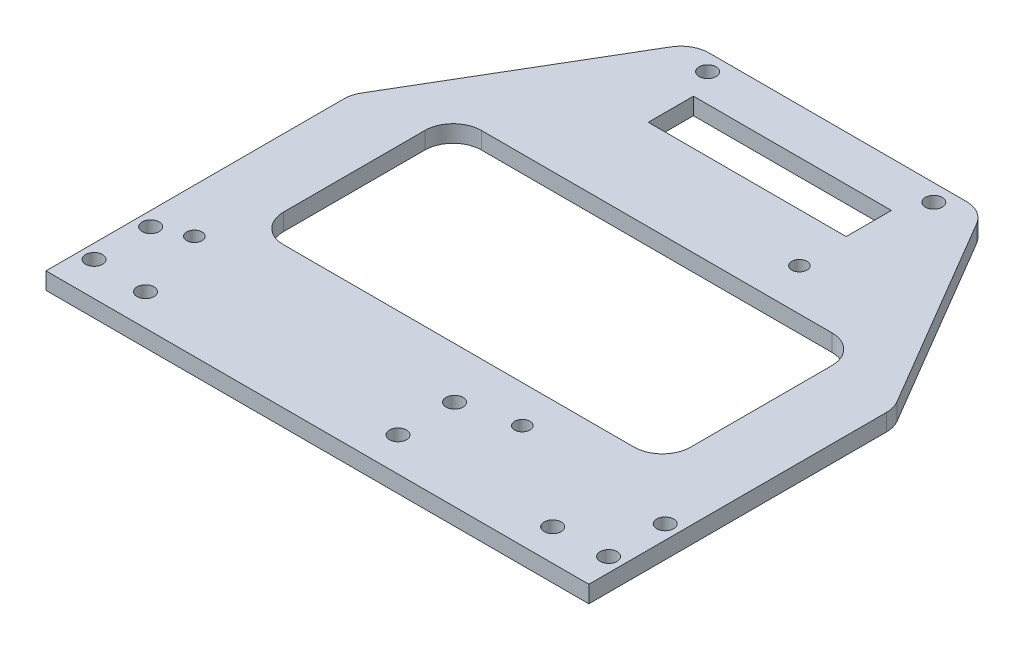
SolidWorks part; units mm, degrees
ref_plane "前基準面" through (0, 0, 0) normal (0, 0, 1) x (1, 0, 0)
ref_plane "上基準面" through (0, 0, 0) normal (0, 1, 0) x (1, 0, 0)
ref_plane "右基準面" through (0, 0, 0) normal (1, 0, 0) x (0, 0, -1)
sketch "Sketch1" plane through (0, 0, 0) normal (0, 1, 0) x (1, 0, 0)
  line L0 (43, -58) -> (48, -58) construction
  line L1 (-48, -80) -> (48, -80) construction
  line L2 (-48, -80) -> (-48, 80)
  line L3 (-48, 80) -> (48, 80)
  line L4 (48, -80) -> (48, 80)
  line L5 (0, 80) -> (0, -80) construction
  line L6 (-48, 0) -> (48, 0) construction
  line L7 (-48, -80) -> (48, -80) construction
  line L8 (-48, -80) -> (-48, -96)
  line L9 (-48, -96) -> (48, -96)
  line L10 (48, -80) -> (48, -96)
  line L11 (19.5, -31.4) -> (25.5, -31.4)
  line L12 (19.5, -31.4) -> (19.5, -59.4)
  line L13 (19.5, -59.4) -> (25.5, -59.4)
  line L14 (25.5, -31.4) -> (25.5, -59.4)
  line L15 (43, -80) -> (34.5, -80)
  line L16 (43, -80) -> (43, -31.4) construction
  line L17 (43, -31.4) -> (34.5, -31.4)
  line L18 (34.5, -80) -> (34.5, -31.4)
  line L19 (43, -31.4) -> (43.5, -31.4)
  line L20 (43, -31.4) -> (43, -58) construction
  line L21 (43, -58) -> (43.5, -58)
  line L22 (43.5, -31.4) -> (43.5, -58)
  line L23 (43, -80) -> (43, -58)
  circle A0 centre (45.5, -74) radius 1.5 construction
  circle A1 centre (45.5, -64) radius 1.5 construction
  circle A2 centre (-45.5, -64) radius 1.5 construction
  circle A3 centre (-45.5, -74) radius 1.5 construction
  circle A4 centre (45.5, -74) radius 1.5
  circle A5 centre (45.5, -64) radius 1.5
  circle A6 centre (-45.5, -64) radius 1.5
  circle A7 centre (-45.5, -74) radius 1.5
  circle A8 centre (8.25, -74) radius 1.5 construction
  circle A9 centre (8.25, -64) radius 1.5 construction
  circle A10 centre (8.25, -74) radius 1.5
  circle A11 centre (8.25, -64) radius 1.5
  circle A12 centre (15.3209, -52.5307) radius 1.65 construction
  circle A13 centre (0.2595, -52.5307) radius 1.65 construction
  circle A14 centre (15.3209, -37.4693) radius 1.65 construction
  circle A15 centre (0.2595, -37.4693) radius 1.65 construction
  circle A16 centre (15.3209, -52.5307) radius 1.65 construction
  circle A17 centre (0.2595, -52.5307) radius 1.65 construction
  circle A18 centre (15.3209, -37.4693) radius 1.65 construction
  circle A19 centre (0.2595, -37.4693) radius 1.65 construction
  circle A24 centre (0.2595, -37.4693) radius 1.65
  circle A25 centre (15.3209, -37.4693) radius 1.65
  circle A26 centre (15.3209, -52.5307) radius 1.65
  circle A27 centre (0.2595, -52.5307) radius 1.65
  circle A28 centre (17.55, -90) radius 1.5 construction
  circle A29 centre (17.55, -90) radius 1.5
  circle A30 centre (45.55, -90) radius 1.5 construction
  circle A31 centre (45.55, -90) radius 1.5
  circle A32 centre (-45.55, -90) radius 1.5
  circle A33 centre (-17.55, -90) radius 1.5
  point P0 (0, 0)
  dimension "D4" = 0.5
  dimension "D5" = 6
  dimension "D1" = 96
  dimension "D2" = 160
  dimension "D3" = 16
  dimension "D6" = 28
  dimension "D7" = 22.5
  dimension "D8" = 36.6
  dimension "D9" = 8.5
  dimension "D10" = 48.6
extrude "Boss-Extrude1" add sketch "Sketch1" along normal blind 3
sketch "Sketch3" plane through (0, 3, 0) normal (0, 1, 0) x (1, 0, 0)
  line L0 (0, -96) -> (0, 80) construction
  line L1 (-48, -96) -> (48, -96) construction
  line L2 (48, 80) -> (-48, 80) construction
  line L3 (0, 9) -> (-17.8495, 79.2684) construction
  line L4 (-17.8495, 79.2684) -> (17.8495, 79.2684) construction
  line L5 (0, 9) -> (17.8495, 79.2684) construction
  circle A0 centre (0, 9) radius 5 construction
  circle A1 centre (0, 9) radius 1.5
  circle A2 centre (-17.8495, 79.2684) radius 0.7646 construction
  circle A3 centre (17.8495, 79.2684) radius 1.5 construction
  point P12 (0, 79.2684)
  dimension "D1" = 10
  dimension "D2" = 105
  dimension "D3" = 3
  dimension "D6" = 3
  dimension "D7" = 1.5291
  dimension "D4" = 72.5
  dimension "D5" = 17.8495
extrude "Cut-Extrude2" cut sketch "Sketch3" against normal up to next
sketch "Sketch4" plane through (0, 3, 0) normal (0, 1, 0) x (1, 0, 0)
  line L0 (0, 80) -> (0, 0) construction
  line L1 (48, 80) -> (-48, 80) construction
  line L2 (48, 12) -> (25.605, 12)
  line L3 (-48, 80) -> (-25.605, 80)
  line L4 (-48, 80) -> (-48, 12)
  line L5 (-48, 12) -> (-25.605, 12)
  line L6 (-25.605, 80) -> (-25.605, 12)
  line L7 (25.605, 80) -> (25.605, 12)
  line L8 (48, 80) -> (25.605, 80)
  line L9 (48, 80) -> (48, 12)
  dimension "D1" = 51.21
  dimension "D2" = 68
extrude "Cut-Extrude3" cut sketch "Sketch4" against normal up to next
sketch "Sketch6" plane through (0, 3, 0) normal (0, 1, 0) x (1, 0, 0)
  line L0 (25.605, 80) -> (25.605, 12) construction
  line L1 (-25.605, 80) -> (25.605, 80)
  line L2 (-25.605, 80) -> (-25.605, 85)
  line L3 (-25.605, 85) -> (25.605, 85)
  line L4 (25.605, 80) -> (25.605, 85)
  dimension "D1" = 5
extrude "Boss-Extrude2" add sketch "Sketch6" against normal blind 3
sketch "Sketch7" plane through (0, 3, 0) normal (0, 1, 0) x (1, 0, 0)
  circle A0 centre (-17.8495, 79.2684) radius 1.5
  circle A1 centre (17.8495, 79.2684) radius 1.5
  dimension "D1" = 3
  dimension "D2" = 3
extrude "Cut-Extrude4" cut sketch "Sketch7" against normal up to next
sketch "Sketch9" plane through (0, 3, 0) normal (0, 1, 0) x (1, 0, 0)
  line L2 (25.605, 85) -> (-25.605, 85) construction
  line L4 (-22.6908, 44) -> (-25.605, 44) construction
  line L5 (-25.605, 12) -> (-25.605, 85) construction
  line L6 (-22.6908, 44) -> (-22.6908, 32.9821) construction
  line L7 (0, 85) -> (0, 0) construction
  circle A1 centre (-22.6908, 44) radius 1.5
  circle A2 centre (22.6908, 44) radius 1.5
  dimension "D1" = 3
  dimension "D2" = 41
extrude "Cut-Extrude5" cut sketch "Sketch9" against normal up to next
sketch "Sketch10" plane through (0, 3, 0) normal (0, 1, 0) x (1, 0, 0)
  line L0 (0, 85) -> (0, -96) construction
  line L1 (25.605, 85) -> (-25.605, 85) construction
  line L2 (-48, -96) -> (48, -96) construction
  line L3 (48, -26) -> (25.605, 12)
  line L4 (48, -96) -> (48, 12) construction
  line L5 (48, -26) -> (48, 12)
  line L6 (48, 12) -> (25.605, 12)
  line L7 (-48, -26) -> (-48, 12)
  line L8 (-48, -26) -> (-25.605, 12)
  line L9 (-48, 12) -> (-25.605, 12)
  dimension "D1" = 38
extrude "Cut-Extrude6" cut sketch "Sketch10" against normal up to next
sketch "Sketch11" plane through (0, 0, 0) normal (0, -1, 0) x (1, 0, 0)
  line L0 (-25.605, -52.6413) -> (-45.8738, -40.3515)
  line L1 (-45.8738, -40.3515) -> (-25.605, -52.6413) construction
  line L2 (-42.8854, -33.0371) -> (-31.7967, -35.6413)
  line L3 (-31.7967, -35.6413) -> (-25.605, -35.6413)
  line L4 (-16.2499, -35.6413) -> (-31.7967, -35.6413) construction
  line L5 (-25.605, -35.6413) -> (-25.605, -52.6413)
  line L6 (0, 0) -> (0, -85) construction
  line L7 (42.8854, -33.0371) -> (31.7967, -35.6413)
  line L8 (25.605, -12) -> (48, 26)
  line L9 (48, 26) -> (48, 96)
  line L10 (48, 96) -> (-48, 96)
  line L11 (-48, 96) -> (-48, 26)
  line L12 (-48, 26) -> (-25.605, -12)
  line L13 (-25.605, -12) -> (-25.605, -85)
  line L14 (-25.605, -85) -> (25.605, -85)
  line L15 (25.605, -85) -> (25.605, -12)
  line L16 (25.605, -12) -> (48, 26)
  line L17 (48, 26) -> (48, 96)
  line L18 (48, 96) -> (-48, 96)
  line L19 (-48, 96) -> (-48, 26)
  line L20 (-48, 26) -> (-25.605, -12)
  line L21 (-25.605, -12) -> (-25.605, -85)
  line L22 (-25.605, -85) -> (25.605, -85)
  line L23 (25.605, -85) -> (25.605, -12)
  line L24 (31.7967, -35.6413) -> (25.605, -35.6413)
  line L25 (25.605, -35.6413) -> (25.605, -52.6413)
  line L26 (25.605, -52.6413) -> (45.8738, -40.3515)
  arc A0 (-45.8738, -40.3515) -> (-42.8854, -33.0371) centre (-43.7999, -36.9312) cw
  circle A1 centre (-43.7999, -36.9312) radius 2.5
  circle A2 centre (-32.9303, -41.9312) radius 1.5
  circle A3 centre (32.9303, -41.9312) radius 1.5
  circle A4 centre (43.7999, -36.9312) radius 2.5
  arc A5 (45.8738, -40.3515) -> (42.8854, -33.0371) centre (43.7999, -36.9312) ccw
  line M26 (-25.605, -12) -> (-25.605, -85)
  dimension "D2" = 5
  dimension "D3" = 3
  dimension "D1" = 0
extrude "Boss-Extrude3" add sketch "Sketch11" against normal blind 3 contours A0 L0 L3 L2 A2 A1 M26 | L26 A5 L7 L24 L23 A4 A3
sketch "Sketch12" plane through (0, 0, 0) normal (0, -1, 0) x (1, 0, 0)
  line L0 (11.4001, -53.9413) -> (11.4001, -38.6413) construction
  line L1 (11.4001, -38.6413) -> (16.2501, -38.6413) construction
  line L2 (16.2501, -38.6413) -> (16.3501, -32.8413) construction
  line L3 (16.3501, -32.8413) -> (11.4001, -32.8413) construction
  line L4 (11.4001, -32.8413) -> (11.4001, -31.1913) construction
  line L5 (11.4001, -31.1913) -> (11.4001, -25.1913) construction
  line L6 (11.4001, -25.1913) -> (5.4001, -25.1913) construction
  line L7 (11.4001, -25.1913) -> (11.4001, -19.8913) construction
  line L8 (11.4001, -19.8913) -> (-2.9999, -19.8913) construction
  line L9 (-2.9999, -19.8913) -> (-2.9999, -31.1913) construction
  line L10 (-11.0999, -31.1913) -> (5.4001, -31.1913) construction
  line L11 (-2.9999, -31.1913) -> (-11.0999, -31.1913) construction
  line L12 (-11.0999, -31.1913) -> (-11.0999, -32.8413) construction
  line L13 (-11.0999, -32.8413) -> (-16.0499, -32.8413) construction
  line L14 (-16.0499, -32.8413) -> (-16.0499, -38.6413) construction
  line L15 (-15.2499, -38.6413) -> (-16.2499, -38.6413) construction
  line L16 (-16.0499, -38.6413) -> (-11.0999, -38.6413) construction
  line L17 (-11.0999, -53.9413) -> (-11.0999, -35.6413) construction
  line L18 (-11.0999, -38.6413) -> (-11.0999, -53.9413) construction
  line L19 (-11.0999, -53.9413) -> (11.4001, -53.9413) construction
  line L20 (-11.8999, -39.4413) -> (-11.8999, -54.7413)
  line L21 (-11.8999, -54.7413) -> (12.2001, -54.7413)
  line L22 (12.2001, -54.7413) -> (12.2001, -39.4413)
  line L23 (12.2001, -39.4413) -> (17.0364, -39.4413)
  line L24 (17.0364, -39.4413) -> (17.164, -32.0413)
  line L25 (17.164, -32.0413) -> (12.2001, -32.0413)
  line L26 (12.2001, -32.0413) -> (12.2001, -31.1913)
  line L27 (12.2001, -31.1913) -> (12.2001, -25.1913)
  line L28 (12.2001, -25.1913) -> (12.2001, -19.0913)
  line L29 (12.2001, -19.0913) -> (-3.7999, -19.0913)
  line L30 (-3.7999, -19.0913) -> (-3.7999, -30.3913)
  line L31 (-3.7999, -30.3913) -> (-11.8999, -30.3913)
  line L32 (-11.8999, -30.3913) -> (-11.8999, -32.0413)
  line L33 (-11.8999, -32.0413) -> (-16.8499, -32.0413)
  line L34 (-16.8499, -32.0413) -> (-16.8499, -39.4413)
  line L35 (-16.8499, -39.4413) -> (-11.8999, -39.4413)
  dimension "D2" = 16
  dimension "D3" = 11.3
  dimension "D1" = 0.8
extrude "Cut-Extrude7" cut sketch "Sketch12" against normal up to next
sketch "Sketch13" plane through (0, 0, 0) normal (0, -1, 0) x (1, 0, 0)
  line L0 (-11.8999, -39.4413) -> (-11.8999, -54.7413) construction
  line L1 (-16.8499, -29.0413) -> (-11.8999, -29.0413)
  line L2 (-16.8499, -29.0413) -> (-16.8499, -44.0413)
  line L3 (-16.8499, -44.0413) -> (-11.8999, -44.0413)
  line L4 (-11.8999, -29.0413) -> (-11.8999, -44.0413)
  line L5 (-16.8499, -32.0413) -> (-16.8499, -39.4413) construction
  line L6 (-11.8999, -32.0413) -> (-16.8499, -32.0413) construction
  line L7 (0.1501, -54.7413) -> (0.1501, -13.9321) construction
  line L8 (-11.8999, -54.7413) -> (12.2001, -54.7413) construction
  line L9 (17.1501, -29.0413) -> (17.1501, -44.0413)
  line L10 (17.1501, -29.0413) -> (12.2001, -29.0413)
  line L11 (12.2001, -29.0413) -> (12.2001, -44.0413)
  line L12 (17.1501, -44.0413) -> (12.2001, -44.0413)
  line L13 (12.2001, -54.7413) -> (12.2001, -39.4413) construction
  line L14 (12.2001, -51.376) -> (18.2789, -51.376)
  line L15 (12.2001, -51.376) -> (12.2001, -46.608)
  line L16 (12.2001, -46.608) -> (18.2789, -46.608)
  line L17 (18.2789, -51.376) -> (18.2789, -46.608)
  dimension "D1" = 3
  dimension "D2" = 15
extrude "Cut-Extrude8" cut sketch "Sketch13" against normal up to next
sketch "Sketch14" plane through (0, 0, 0) normal (0, -1, 0) x (1, 0, 0)
  line L0 (0, -85) -> (0, 0) construction
  line L1 (25.605, -85) -> (-25.605, -85) construction
  line L2 (25.605, -85) -> (25.605, -72)
  line L3 (70, -72) -> (-70, -72)
  line L4 (70, -72) -> (70, -77)
  line L5 (62, -85) -> (-62, -85)
  line L6 (-70, -72) -> (-70, -77)
  line L7 (0, -85) -> (0, -72) construction
  line L8 (70, -74.5) -> (-70, -74.5) construction
  line L9 (-25.605, -85) -> (-25.605, -72)
  arc A0 (70, -77) -> (62, -85) centre (62, -77) cw
  arc A1 (-62, -85) -> (-70, -77) centre (-62, -77) cw
  point P5 (0, -74.5)
  point P15 (70, -85)
  point P18 (-70, -85)
  dimension "D3" = 8
  dimension "D1" = 13
  dimension "D2" = 140
extrude "Boss-Extrude4" add sketch "Sketch14" against normal blind 3 contours A1 L5 L9 L3 L6 | A0 L4 L3 L2 L5
sketch "Sketch15" plane through (0, 3, 0) normal (0, 1, 0) x (1, 0, 0)
  line L0 (0, 0) -> (0, 85) construction
  line L1 (62, 85) -> (-62, 85) construction
  line L2 (20, 9) -> (-20, 9) construction
  circle A0 centre (-20, 9) radius 1.5
  circle A1 centre (20, 9) radius 1.5
  point P9 (0, 9)
  dimension "D2" = 3
  dimension "D1" = 40
extrude "Cut-Extrude9" cut sketch "Sketch15" against normal up to next
sketch "Sketch18" plane through (0, 3, 0) normal (0, 1, 0) x (1, 0, 0)
  line L0 (-25.605, 12) -> (25.605, 12)
  line L2 (83.0825, 12) -> (-87.9318, 12)
  line L3 (83.0825, 12) -> (83.0825, 92.1136)
  line L4 (83.0825, 92.1136) -> (-87.9318, 92.1136)
  line L5 (-87.9318, 12) -> (-87.9318, 92.1136)
extrude "Cut-Extrude10" cut sketch "Sketch18" against normal through all contours L5 L2 L0 L3 L4
sketch "Sketch19" plane through (0, 3, 0) normal (0, 1, 0) x (1, 0, 0)
  line L1 (43.5, -31.4) -> (34.5, -31.4)
  line L2 (43.5, -31.4) -> (43.5, -80)
  line L3 (43.5, -80) -> (34.5, -80)
  line L4 (34.5, -31.4) -> (34.5, -80)
  line L5 (25.5, -31.4) -> (-5.9684, -31.4)
  line L6 (25.5, -31.4) -> (25.5, -59.4519)
  line L7 (25.5, -59.4519) -> (-5.9684, -59.4519)
  line L8 (-5.9684, -31.4) -> (-5.9684, -59.4519)
extrude "Boss-Extrude5" add sketch "Sketch19" against normal through all
sketch "Sketch20" plane through (0, 3, 0) normal (0, 1, 0) x (1, 0, 0)
  line L0 (48, -96) -> (48, -26) construction
  line L1 (-48, -96) -> (48, -96)
  line L2 (-48, -96) -> (-48, -80)
  line L3 (-48, -80) -> (48, -80)
  line L4 (48, -96) -> (48, -80)
  dimension "D1" = 16
extrude "Cut-Extrude11" cut sketch "Sketch20" against normal through all
sketch "Sketch22" plane through (0, 3, 0) normal (0, 1, 0) x (1, 0, 0)
  line L1 (-2.0718, 7.1965) -> (2.0718, 7.1965)
  line L2 (-2.0718, 7.1965) -> (-2.0718, 10.8035)
  line L3 (-2.0718, 10.8035) -> (2.0718, 10.8035)
  line L4 (2.0718, 7.1965) -> (2.0718, 10.8035)
  line L5 (0, 10.8035) -> (0, 7.1965) construction
  line L6 (-2.0718, 9) -> (2.0718, 9) construction
  point P0 (0, 9)
extrude "Boss-Extrude6" add sketch "Sketch22" against normal through all
fillet "Fillet1" radius 5 4 edges at (-48, 1.5, 26) (-25.605, 1.5, -12) (48, 1.5, 26) (25.605, 1.5, -12)
sketch "Sketch23" plane through (0, 3, 0) normal (0, 1, 0) x (1, 0, 0)
  circle A0 centre (-40.1706, -61.5904) radius 1.35
  circle A1 centre (17.8294, -61.5904) radius 1.35
  circle A2 centre (17.8294, -12.5904) radius 1.35
extrude "Cut-Extrude12" cut sketch "Sketch23" against normal through all
sketch "Sketch24" plane through (0, 3, 0) normal (0, 1, 0) x (1, 0, 0)
  line L0 (0, -80) -> (0, 12) construction
  line L1 (48, -80) -> (-48, -80) construction
  line L2 (22.748, 12) -> (-22.748, 12) construction
  line L4 (31, -55) -> (-31, -55)
  line L5 (36, -50) -> (36, -25)
  line L6 (31, -20) -> (-31, -20)
  line L7 (-36, -50) -> (-36, -25)
  line L8 (0, -20) -> (0, -55) construction
  line L9 (36, -37.5) -> (-36, -37.5) construction
  arc A0 (31, -55) -> (36, -50) centre (31, -50) ccw
  arc A1 (36, -25) -> (31, -20) centre (31, -25) ccw
  arc A2 (-31, -20) -> (-36, -25) centre (-31, -25) ccw
  arc A3 (-31, -55) -> (-36, -50) centre (-31, -50) cw
  point P6 (0, -37.5)
  point P12 (36, -55)
  point P15 (36, -20)
  point P18 (-36, -20)
  dimension "D4" = 5
  dimension "D1" = 72
  dimension "D2" = 35
  dimension "D3" = 32
extrude "Cut-Extrude13" cut sketch "Sketch24" against normal through all
sketch "Sketch28" plane through (0, 3, 0) normal (0, 1, 0) x (1, 0, 0)
  line L0 (0, -80) -> (0, 12) construction
  line L1 (48, -80) -> (-48, -80) construction
  line L2 (22.748, 12) -> (-22.748, 12) construction
  line L4 (17.5, 4) -> (-17.5, 4)
  line L5 (17.5, 4) -> (17.5, -4)
  line L6 (17.5, -4) -> (-17.5, -4)
  line L7 (-17.5, 4) -> (-17.5, -4)
  line L8 (0, -4) -> (0, 4) construction
  line L9 (17.5, 0) -> (-17.5, 0) construction
  point P6 (0, 0)
  dimension "D1" = 35
  dimension "D2" = 8
  dimension "D3" = 76
extrude "Cut-Extrude17" cut sketch "Sketch28" against normal through all
sketch "Sketch29" plane through (0, 3, 0) normal (0, 1, 0) x (1, 0, 0)
  line L0 (0, 12) -> (0, -80) construction
  line L1 (22.748, 12) -> (-22.748, 12) construction
  line L2 (48, -80) -> (-48, -80) construction
  line L3 (-48, -27.3637) -> (-48, -80) construction
  circle A0 centre (-36, -74.4) radius 1.5
  circle A1 centre (36, -74.4) radius 1.5
  dimension "D1" = 3
  dimension "D2" = 5.6
  dimension "D3" = 12
extrude "Cut-Extrude18" cut sketch "Sketch29" against normal through all
